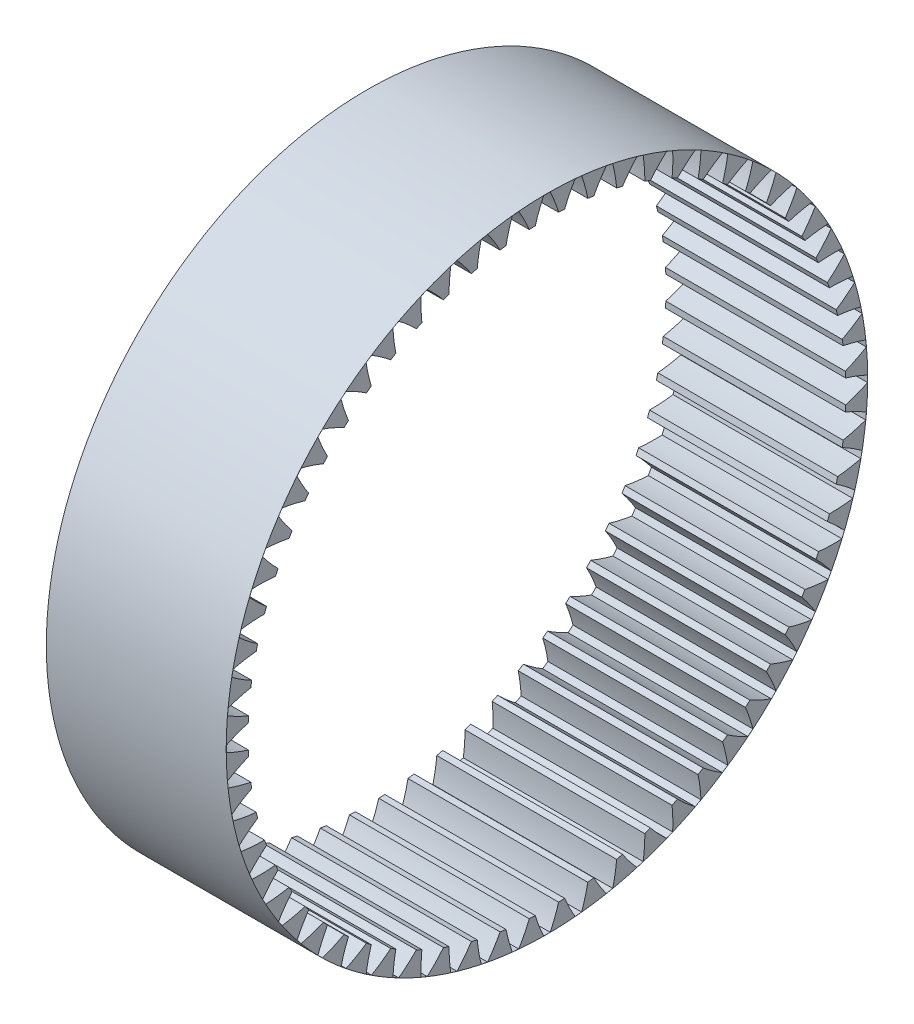
SolidWorks part; units mm, degrees
ref_plane "Plane1" through (0, 0, 0) normal (0, 0, 1) x (1, 0, 0)
ref_plane "Plane2" through (0, 0, 0) normal (0, 1, 0) x (1, 0, 0)
ref_plane "Plane3" through (0, 0, 0) normal (1, 0, 0) x (0, 0, -1)
sketch "HoldingSke" plane through (0, 0, 0) normal (0, 1, 0) x (1, 0, 0)
  line L0 (0, 0) -> (0.2192, -0.4494)
  line L1 (-15, 0) -> (100, 0) construction
  line L2 (0, 0) -> (-2.1039, 2.3779)
  line L3 (0, 0) -> (-11.863, 4.5341)
  line L4 (0, 0) -> (3.7858, 7.762)
  line L5 (0, 0) -> (-23.7986, -8.8762)
  line L6 (0, 0) -> (-10.5278, -7.1032)
  line L7 (-2.1039, 2.3779) -> (3.3635, 27.1825)
  line L8 (-76.2, 4.3779) -> (-54.61, 4.3779)
  line L9 (-71.009, 38.7566) -> (-53.1078, 45.2721)
  line L10 (-76.2, 71.12) -> (104.1128, 71.12)
  line L11 (0, 0) -> (-37.3, 0)
  line L12 (-76.2, 101.6) -> (-76.133, 101.6)
  line L13 (24.9733, 27.94) -> (52.9518, 28.4284)
  line L14 (24.9733, 27.94) -> (24.9743, 27.94)
  line L15 (24.9733, 27.94) -> (100.4006, 29.5858)
  circle A0 centre (0, 0) radius 12.5
  circle A1 centre (0, 0) radius 12.7
  circle A2 centre (0, 0) radius 12.7
  dimension "MHD" = 25.4
  dimension "Hub_dia" = 25.4
  dimension "Diameter" = 25
  dimension "Num_teeth" = 64
  dimension "Pitch" = 0.5
  dimension "Overall_len" = 25.4
  dimension "Show_teeth" = 64
  dimension "Thickness" = 12.7
  dimension "OAL" = 25.4001
  dimension "T_dim" = 21.59
  dimension "Ap" = 20
  dimension "H" = 19.05
  dimension "Pitch_radius" = 180.3128
  dimension "Width" = 37.3
  dimension "Backlash" = 0.067
  dimension "Addendum_fac" = 1
  dimension "Dedendum_fac" = 1.25
  dimension "Clearance_fac" = 0.25
  dimension "Dedendum_add" = 0.001
  dimension "Module" = 2
sketch "BasProSke" plane through (0, 0, 0) normal (0, 1, 0) x (1, 0, 0)
  line L0 (-10, 0) -> (60, 0) construction
  line L1 (0, 62) -> (0, 66.5264)
  line L2 (0, 62) -> (37.3, 62)
  line L3 (37.3, 62) -> (37.3, 66.5264)
  line L4 (37.3, 66.5264) -> (0, 66.5264)
  dimension "Thickness" = 37.3
  dimension "Diameter" = 133.0528
  dimension "Inside_diameter" = 124
revolve "Base-Revolve" add sketch "BasProSke" angle 360 about L0
sketch "TooCutSke" plane through (0, 0, 0) normal (1, 0, 0) x (0, 0, -1)
  line L3 (1.7381, 63.9764) -> (1.7381, 53.6633) construction
  line L4 (0, 0) -> (0, 59.563) construction
  line L5 (0, 0) -> (-3.3527, 68.2452) construction
  line L6 (-28.2481, 52.8038) -> (35.1414, 55.918) construction
  circle A0 centre (0, 0) radius 64 construction
  circle A1 centre (0, 0) radius 66.501 construction
  circle A2 centre (0, 0) radius 54.1263 construction
  circle A3 centre (0, 0) radius 61.9746 construction
  arc A4 (2.4238, 61.9272) -> (0.6739, 66.4976) centre (-28.2481, 52.8038) ccw
  arc A5 (2.4238, 61.9272) -> (-2.4238, 61.9272) centre (0, 0) ccw
  arc A6 (0.6739, 66.4976) -> (-0.6739, 66.4976) centre (0, 0) ccw
  arc A7 (-0.6739, 66.4976) -> (-2.4238, 61.9272) centre (28.2481, 52.8038) ccw
  dimension "Pitch_dia" = 128
  dimension "Base_dia" = 108.2526
  dimension "Root_dia" = 133.002
  dimension "Overcut_dia" = 123.9492
  dimension "Flank_rad" = 32
  dimension "Half_ang" = 2.813
  dimension "Half_CT" = 1.7381
extrude "ToothCut" cut sketch "TooCutSke" along normal through all
fillet "Breaks" [suppressed] radius 0.2
fillet "RootFillets" [suppressed] radius 0.501
pattern_circular "TeethCuts" count 64 every 5.625 about axis through (-10, 0, 0) along (1, 0, 0) of "RootFillets", "Breaks", "ToothCut"
equation "' \"Module@HoldingSke\" = 6.35"
equation "' \"Num_teeth@HoldingSke\" = 24"
equation "' \"Ap@HoldingSke\" =  14.5"
equation "' \"Ap@HoldingSke\" = 14.5"
equation "' \"Width@HoldingSke\" = 12"
equation "' \"Diameter@HoldingSke\" = 8 * 25.4"
equation "' \"Show_teeth@HoldingSke\" = 100"
equation "' \"Backlash@HoldingSke\" = 0.009 * 25.4"
equation "' \"Addendum_fac@HoldingSke\" = 1.0"
equation "' \"Dedendum_fac@HoldingSke\" = 1.25"
equation "' \"Dedendum_add@HoldingSke\" = 0.00005 * 25.4"
equation "' \"Clearance_fac@HoldingSke\" = 0.25"
equation "\"Pitch@HoldingSke\" = 1 / \"Module@HoldingSke\" "
equation "\"Overcut_dia@TooCutSke\" = (\"Num_teeth@HoldingSke\" - 2 * \"Addendum_fac@HoldingSke\") / \"Pitch@HoldingSke\" - 0.002 * 25.4"
equation "\"Pitch_dia@TooCutSke\" = \"Num_teeth@HoldingSke\" / \"Pitch@HoldingSke\""
equation "\"Base_dia@TooCutSke\" = \"Num_teeth@HoldingSke\" / \"Pitch@HoldingSke\" * cos((\"Ap@HoldingSke\"  * 3.14159265 / 180)) * 0.90"
equation "\"Root_dia@TooCutSke\" = \"Num_teeth@HoldingSke\"  / \"Pitch@HoldingSke\" + 2 *  \"Dedendum_fac@HoldingSke\"/ \"Pitch@HoldingSke\" + \"Dedendum_add@HoldingSke\" * 2"
equation "\"Half_ang@TooCutSke\" = 180 / \"Num_teeth@HoldingSke\""
equation "\"Half_CT@TooCutSke\" = \"Num_teeth@HoldingSke\" / \"Pitch@HoldingSke\" * sin((3.14159265 / 2 / \"Num_teeth@HoldingSke\")) / 2 + 10 * \"Backlash@HoldingSke\" / 4"
equation "\"Flank_rad@TooCutSke\" = \"Num_teeth@HoldingSke\" / \"Pitch@HoldingSke\" / 4"
equation "\"Radius@RootFillets\"= \"Clearance_fac@HoldingSke\" / \"Pitch@HoldingSke\" + \"Dedendum_add@HoldingSke\""
equation "\"Break_rad@Breaks\" = 0.02 / \"Pitch@HoldingSke\" * 5"
equation "\"Num_teeth@TeethCuts\" = int( \"Show_teeth@HoldingSke\" ) + 1"
equation "\"Num_teeth@TeethCuts\" = ((sgn( \"Num_teeth@TeethCuts\" - \"Num_teeth@HoldingSke\" )-1)*( \"Num_teeth@TeethCuts\" - \"Num_teeth@HoldingSke\" ))/-2+ \"Num_teeth@HoldingSke\""
equation "\"Num_teeth@TeethCuts\" = ((sgn( \"Num_teeth@TeethCuts\" - 2.0)+1)*( \"Num_teeth@TeethCuts\" - 2.0))/2 +2.0"
equation "\"Angle@TeethCuts\" = 360.0 / \"Num_teeth@HoldingSke\""
equation "\"Diameter@BasProSke\" = \"Num_teeth@HoldingSke\"  / \"Pitch@HoldingSke\" + 2 *  \"Dedendum_fac@HoldingSke\"/ \"Pitch@HoldingSke\" + \"Dedendum_add@HoldingSke\" * 2 + 0.002 * 25.4"
equation "\"Diameter@BasProSke\" = ((sgn( \"Diameter@BasProSke\"  - \"Diameter@HoldingSke\" )+1)*( \"Diameter@BasProSke\"  - \"Diameter@HoldingSke\" ))/2 + \"Diameter@HoldingSke\""
equation "\"Inside_diameter@BasProSke\" =  (\"Num_teeth@HoldingSke\" - 2 * \"Addendum_fac@HoldingSke\") / \"Pitch@HoldingSke\" "
equation "\"Thickness@BasProSke\"  = \"Width@HoldingSke\""
